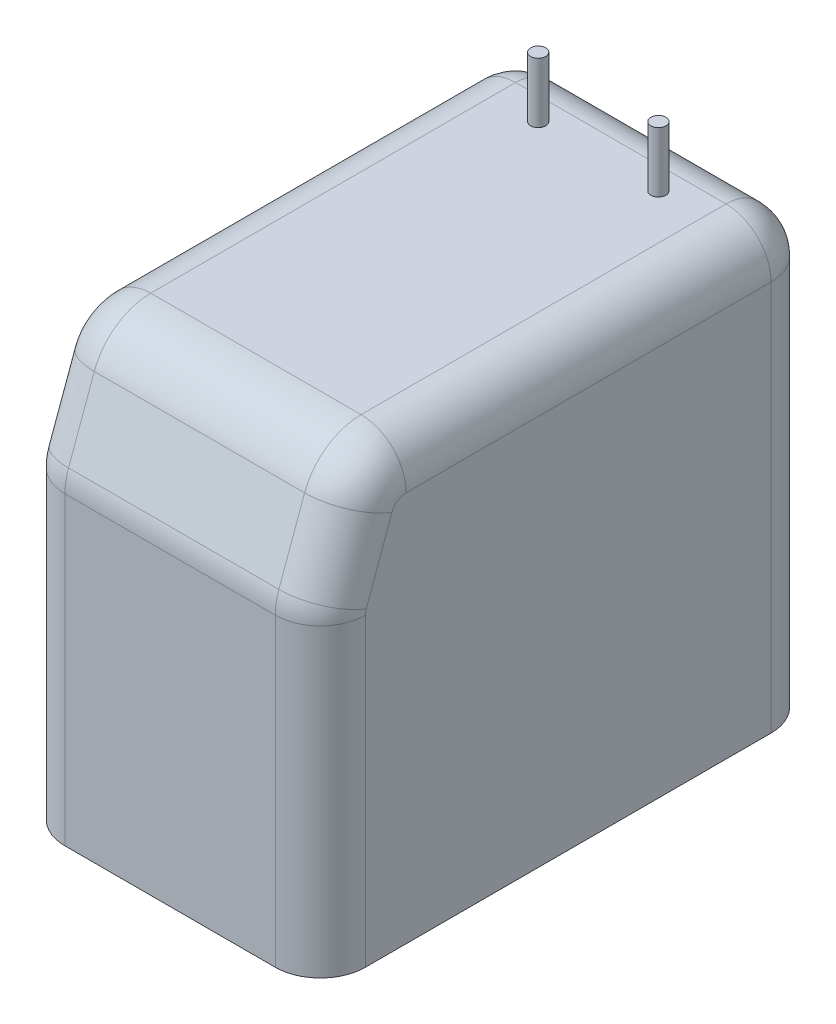
SolidWorks part; units mm, degrees
material "ABS"
ref_plane "Front" through (0, 0, 0) normal (0, 0, 1) x (1, 0, 0)
ref_plane "Top" through (0, 0, 0) normal (0, 1, 0) x (1, 0, 0)
ref_plane "Right" through (0, 0, 0) normal (1, 0, 0) x (0, 0, -1)
sketch "Sketch1" plane through (0, 0, 0) normal (0, 1, 0) x (1, 0, 0)
  line L1 (-127, 209.55) -> (127, 209.55)
  line L2 (-127, 209.55) -> (-127, -209.55)
  line L3 (-127, -209.55) -> (127, -209.55)
  line L4 (127, 209.55) -> (127, -209.55)
  line L5 (-127, 209.55) -> (127, -209.55) construction
  line L6 (-127, -209.55) -> (127, 209.55) construction
  point P0 (0, 0)
  dimension "D1" = 419.1
  dimension "D2" = 254
extrude "Boss-Extrude1" add sketch "Sketch1" along normal blind 368.3
chamfer "Chamfer1" distance 101.6 angle 20 1 edges at (0, 368.3, 209.55)
fillet "Fillet1" radius 50.8 2 edges at (0, 266.7, 209.55) (0, 368.3, 172.5706)
sketch "Sketch2" plane through (0, 368.3, 0) normal (0, 1, 0) x (1, 0, 0)
  line L0 (0, 0) -> (0, 152.4) construction
  line L1 (0, 152.4) -> (-50.8, 152.4) construction
  line L2 (0, 152.4) -> (50.8, 152.4) construction
  circle A0 centre (-50.8, 152.4) radius 6.35
  circle A1 centre (50.8, 152.4) radius 6.35
  dimension "D1" = 12.7
  dimension "D2" = 101.6
  dimension "D3" = 152.4
extrude "Boss-Extrude2" add sketch "Sketch2" along normal blind 50.8
fillet "Fillet2" radius 38.1 10 edges at (-127, 368.3, -36.275) (-127, 359.1129, 166.1378) (-127, 304.9959, 195.6114) (-127, 266.5639, 208.7782) (127, 368.3, -36.275) (127, 359.1129, 166.1378) (127, 304.9959, 195.6114) (127, 266.5639, 208.7782) (-127, 128.8713, 209.55) (127, 128.8713, 209.55)
fillet "Fillet3" radius 38.1 5 edges at (-127, 165.1, -209.55) (-115.8408, 357.1408, -209.55) (0, 368.3, -209.55) (115.8408, 357.1408, -209.55) (127, 165.1, -209.55)
